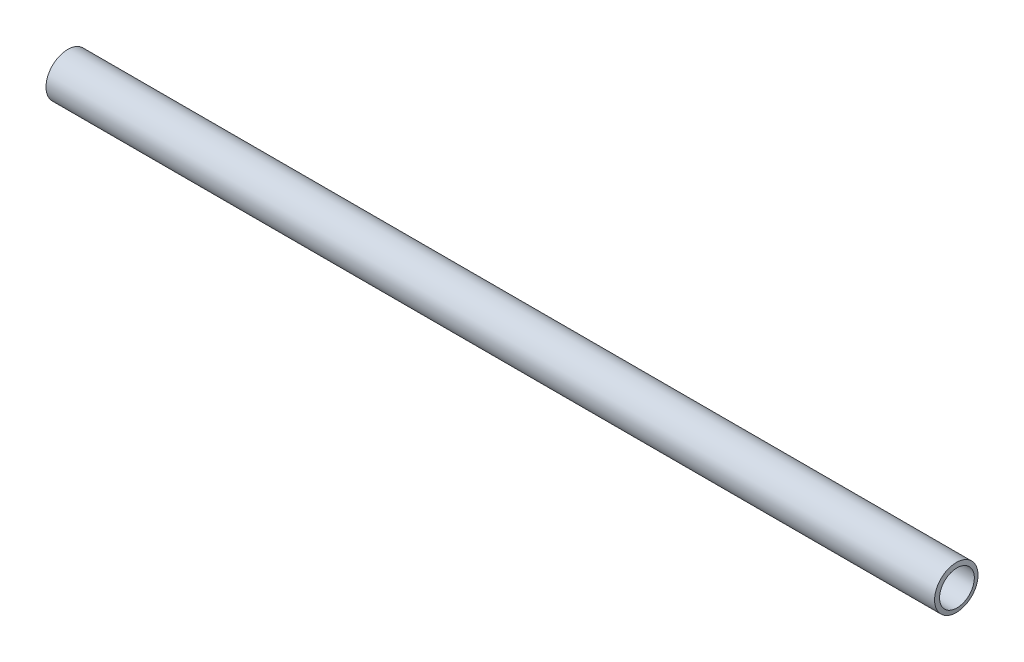
SolidWorks part; units mm, degrees
ref_plane "Front Plane" through (0, 0, 0) normal (0, 0, 1) x (1, 0, 0)
ref_plane "Top Plane" through (0, 0, 0) normal (0, 1, 0) x (1, 0, 0)
ref_plane "Right Plane" through (0, 0, 0) normal (1, 0, 0) x (0, 0, -1)
sketch "Sketch1" plane through (0, 0, 0) normal (0, 0, 1) x (1, 0, 0)
  line L0 (0, 0) -> (-152.4, 0) construction
  line L1 (-152.4, 0) -> (-266.7, 0) construction
  line L2 (-266.7, 0) -> (-520.7, 0) construction
  line L3 (0, 10.16) -> (-152.4, 10.16)
  line L4 (-152.4, 10.16) -> (-266.7, 10.16)
  line L5 (-266.7, 10.16) -> (-520.7, 10.16)
  line L6 (0, 12.7) -> (-152.4, 12.7)
  line L7 (-152.4, 12.7) -> (-266.7, 12.7)
  line L8 (-266.7, 12.7) -> (-520.7, 12.7)
  line L9 (-520.7, 0) -> (-520.7, 12.7)
  line L10 (0, 0) -> (0, 12.7)
  circle A0 centre (-76.2, 0) radius 76.2
  dimension "D1" = 152.4
  dimension "D2" = 114.3
  dimension "D3" = 254
  dimension "D4" = 10.16
  dimension "D5" = 12.7
revolve "Revolve1" add sketch "Sketch1" angle 360 about L2
